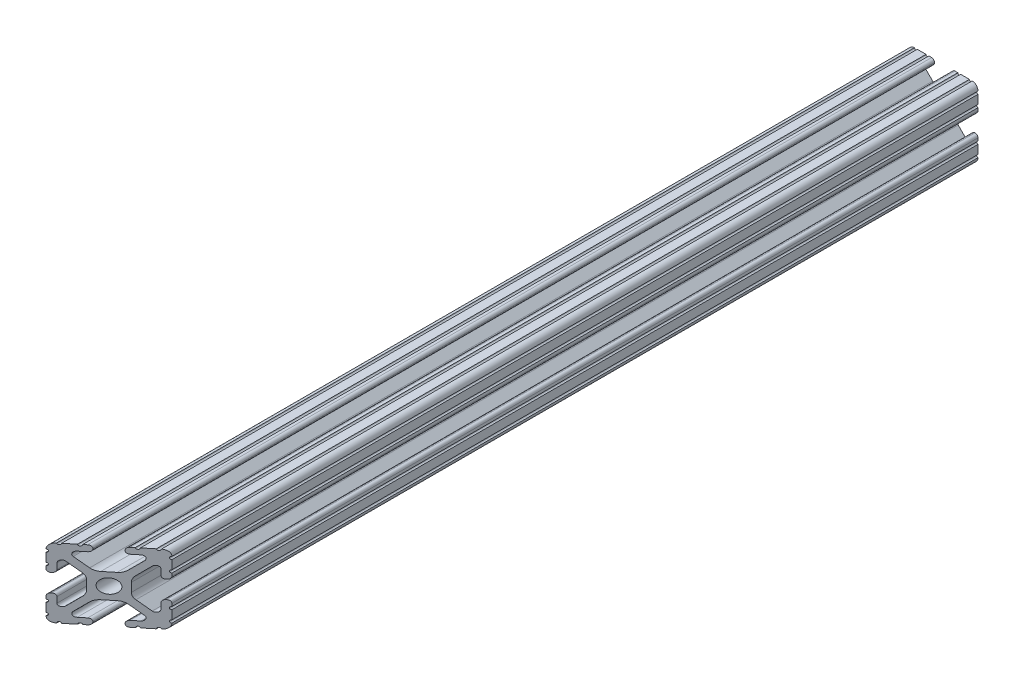
SolidWorks part; units mm, degrees
ref_plane "Front Plane" through (0, 0, 0) normal (0, 0, 1) x (1, 0, 0)
ref_plane "Top Plane" through (0, 0, 0) normal (0, 1, 0) x (1, 0, 0)
ref_plane "Right Plane" through (0, 0, 0) normal (1, 0, 0) x (0, 0, -1)
sketch "Sketch1" plane through (0, 0, 0) normal (0, 0, 1) x (1, 0, 0)
  line L88 (-7.1797, -8.6452) -> (-3.9523, -5.4237)
  line L89 (-1.7093, -4.4958) -> (1.7093, -4.4958)
  line L90 (3.9523, -5.4237) -> (7.1797, -8.6452)
  line L91 (6.4164, -10.4902) -> (4.2875, -10.4902)
  line L92 (3.2385, -11.5392) -> (3.2385, -11.651)
  line L93 (4.2875, -12.7) -> (5.3171, -12.7)
  line L94 (6.3331, -12.7) -> (9.5504, -12.7)
  line L95 (12.7, -9.5504) -> (12.7, -6.3331)
  line L96 (12.7, -5.3171) -> (12.7, -4.2875)
  line L97 (11.651, -3.2385) -> (11.5392, -3.2385)
  line L98 (10.4902, -4.2875) -> (10.4902, -6.4021)
  line L99 (8.7371, -7.1294) -> (5.441, -3.8408)
  line L100 (4.5085, -1.5932) -> (4.5085, 1.5932)
  line L101 (5.441, 3.8408) -> (8.7371, 7.1294)
  line L102 (10.4902, 6.4021) -> (10.4902, 4.2875)
  line L103 (11.5392, 3.2385) -> (11.651, 3.2385)
  line L104 (12.7, 4.2875) -> (12.7, 5.3171)
  line L105 (12.7, 6.3331) -> (12.7, 9.5504)
  line L106 (9.5504, 12.7) -> (6.3331, 12.7)
  line L107 (5.3171, 12.7) -> (4.2875, 12.7)
  line L108 (3.2385, 11.651) -> (3.2385, 11.5392)
  line L109 (4.2875, 10.4902) -> (6.4768, 10.4902)
  line L110 (7.207, 8.7244) -> (3.8983, 5.4232)
  line L111 (1.6558, 4.4958) -> (-1.6558, 4.4958)
  line L112 (-3.8983, 5.4232) -> (-7.207, 8.7244)
  line L113 (-6.4768, 10.4902) -> (-4.2875, 10.4902)
  line L114 (-3.2385, 11.5392) -> (-3.2385, 11.651)
  line L115 (-4.2875, 12.7) -> (-5.3171, 12.7)
  line L116 (-6.3331, 12.7) -> (-9.5504, 12.7)
  line L117 (-12.7, 9.5504) -> (-12.7, 6.3331)
  line L118 (-12.7, 5.3171) -> (-12.7, 4.2875)
  line L119 (-11.651, 3.2385) -> (-11.5392, 3.2385)
  line L120 (-10.4902, 4.2875) -> (-10.4902, 6.4021)
  line L121 (-8.7371, 7.1294) -> (-5.441, 3.8408)
  line L122 (-4.5085, 1.5932) -> (-4.5085, -1.5932)
  line L123 (-5.441, -3.8408) -> (-8.7371, -7.1294)
  line L124 (-10.4902, -6.4021) -> (-10.4902, -4.2875)
  line L125 (-11.5392, -3.2385) -> (-11.651, -3.2385)
  line L126 (-12.7, -4.2875) -> (-12.7, -5.3171)
  line L127 (-12.7, -6.3331) -> (-12.7, -9.5504)
  line L128 (-9.5504, -12.7) -> (-6.3331, -12.7)
  line L129 (-5.3171, -12.7) -> (-4.2875, -12.7)
  line L130 (-3.2385, -11.651) -> (-3.2385, -11.5392)
  line L131 (-4.2875, -10.4902) -> (-6.4164, -10.4902)
  circle A1 centre (0, 0) radius 2.6035
  arc A104 (-7.1797, -8.6452) -> (-6.4164, -10.4902) centre (-6.4164, -9.4098) ccw
  arc A105 (-1.7093, -4.4958) -> (-3.9523, -5.4237) centre (-1.7093, -7.6708) ccw
  arc A106 (3.9523, -5.4237) -> (1.7093, -4.4958) centre (1.7093, -7.6708) ccw
  arc A107 (6.4164, -10.4902) -> (7.1797, -8.6452) centre (6.4164, -9.4098) ccw
  arc A108 (4.2875, -10.4902) -> (3.2385, -11.5392) centre (4.2875, -11.5392) ccw
  arc A109 (3.2385, -11.651) -> (4.2875, -12.7) centre (4.2875, -11.651) ccw
  arc A110 (6.3331, -12.7) -> (5.3171, -12.7) centre (5.8251, -12.7) ccw
  arc A111 (10.5664, -12.6998) -> (9.5504, -12.7) centre (10.0584, -12.7) ccw
  arc A112 (10.5664, -12.6998) -> (12.6998, -10.5664) centre (10.5918, -10.5918) ccw
  arc A113 (12.7, -9.5504) -> (12.6998, -10.5664) centre (12.7, -10.0584) ccw
  arc A114 (12.7, -5.3171) -> (12.7, -6.3331) centre (12.7, -5.8251) ccw
  arc A115 (12.7, -4.2875) -> (11.651, -3.2385) centre (11.651, -4.2875) ccw
  arc A116 (11.5392, -3.2385) -> (10.4902, -4.2875) centre (11.5392, -4.2875) ccw
  arc A117 (8.7371, -7.1294) -> (10.4902, -6.4021) centre (9.4628, -6.4021) ccw
  arc A118 (4.5085, -1.5932) -> (5.441, -3.8408) centre (7.6835, -1.5932) ccw
  arc A119 (5.441, 3.8408) -> (4.5085, 1.5932) centre (7.6835, 1.5932) ccw
  arc A120 (10.4902, 6.4021) -> (8.7371, 7.1294) centre (9.4628, 6.4021) ccw
  arc A121 (10.4902, 4.2875) -> (11.5392, 3.2385) centre (11.5392, 4.2875) ccw
  arc A122 (11.651, 3.2385) -> (12.7, 4.2875) centre (11.651, 4.2875) ccw
  arc A123 (12.7, 6.3331) -> (12.7, 5.3171) centre (12.7, 5.8251) ccw
  arc A124 (12.6998, 10.5664) -> (12.7, 9.5504) centre (12.7, 10.0584) ccw
  arc A125 (12.6998, 10.5664) -> (10.5664, 12.6998) centre (10.5918, 10.5918) ccw
  arc A126 (9.5504, 12.7) -> (10.5664, 12.6998) centre (10.0584, 12.7) ccw
  arc A127 (5.3171, 12.7) -> (6.3331, 12.7) centre (5.8251, 12.7) ccw
  arc A128 (4.2875, 12.7) -> (3.2385, 11.651) centre (4.2875, 11.651) ccw
  arc A129 (3.2385, 11.5392) -> (4.2875, 10.4902) centre (4.2875, 11.5392) ccw
  arc A130 (7.207, 8.7244) -> (6.4768, 10.4902) centre (6.4768, 9.4563) ccw
  arc A131 (1.6558, 4.4958) -> (3.8983, 5.4232) centre (1.6558, 7.6708) ccw
  arc A132 (-3.8983, 5.4232) -> (-1.6558, 4.4958) centre (-1.6558, 7.6708) ccw
  arc A133 (-6.4768, 10.4902) -> (-7.207, 8.7244) centre (-6.4768, 9.4563) ccw
  arc A134 (-4.2875, 10.4902) -> (-3.2385, 11.5392) centre (-4.2875, 11.5392) ccw
  arc A135 (-3.2385, 11.651) -> (-4.2875, 12.7) centre (-4.2875, 11.651) ccw
  arc A136 (-6.3331, 12.7) -> (-5.3171, 12.7) centre (-5.8251, 12.7) ccw
  arc A137 (-10.5664, 12.6998) -> (-9.5504, 12.7) centre (-10.0584, 12.7) ccw
  arc A138 (-10.5664, 12.6998) -> (-12.6998, 10.5664) centre (-10.5918, 10.5918) ccw
  arc A139 (-12.7, 9.5504) -> (-12.6998, 10.5664) centre (-12.7, 10.0584) ccw
  arc A140 (-12.7, 5.3171) -> (-12.7, 6.3331) centre (-12.7, 5.8251) ccw
  arc A141 (-12.7, 4.2875) -> (-11.651, 3.2385) centre (-11.651, 4.2875) ccw
  arc A142 (-11.5392, 3.2385) -> (-10.4902, 4.2875) centre (-11.5392, 4.2875) ccw
  arc A143 (-8.7371, 7.1294) -> (-10.4902, 6.4021) centre (-9.4628, 6.4021) ccw
  arc A144 (-4.5085, 1.5932) -> (-5.441, 3.8408) centre (-7.6835, 1.5932) ccw
  arc A145 (-5.441, -3.8408) -> (-4.5085, -1.5932) centre (-7.6835, -1.5932) ccw
  arc A146 (-10.4902, -6.4021) -> (-8.7371, -7.1294) centre (-9.4628, -6.4021) ccw
  arc A147 (-10.4902, -4.2875) -> (-11.5392, -3.2385) centre (-11.5392, -4.2875) ccw
  arc A148 (-11.651, -3.2385) -> (-12.7, -4.2875) centre (-11.651, -4.2875) ccw
  arc A149 (-12.7, -6.3331) -> (-12.7, -5.3171) centre (-12.7, -5.8251) ccw
  arc A150 (-12.6998, -10.5664) -> (-12.7, -9.5504) centre (-12.7, -10.0584) ccw
  arc A151 (-12.6998, -10.5664) -> (-10.5664, -12.6998) centre (-10.5918, -10.5918) ccw
  arc A152 (-9.5504, -12.7) -> (-10.5664, -12.6998) centre (-10.0584, -12.7) ccw
  arc A153 (-5.3171, -12.7) -> (-6.3331, -12.7) centre (-5.8251, -12.7) ccw
  arc A154 (-4.2875, -12.7) -> (-3.2385, -11.651) centre (-4.2875, -11.651) ccw
  arc A155 (-3.2385, -11.5392) -> (-4.2875, -10.4902) centre (-4.2875, -11.5392) ccw
extrude "Boss-Extrude1" add sketch "Sketch1" along normal mid plane 381
sketch "Sketch2" plane through (0, 12.7, 0) normal (0, 1, 0) x (1, 0, 0)
  line L0 (-12.7, -190.5) -> (-12.7, 190.5) construction
  line L1 (-6.3331, -190.5) -> (-9.5504, -190.5) construction
  line L2 (9.5504, -190.5) -> (6.3331, -190.5) construction
  line L3 (12.7, -190.5) -> (12.7, 190.5) construction
  line L4 (-12.7, -190.5) -> (-12.7, 190.5) construction
  line L5 (-6.3331, -190.5) -> (-9.5504, -190.5) construction
  line L6 (9.5504, -190.5) -> (6.3331, -190.5) construction
  line L7 (12.7, -190.5) -> (12.7, 190.5) construction
  line L8 (12.7, -190.5) -> (-12.7, -190.5)
  line L9 (-12.7, -190.5) -> (-12.7, -125.5716)
  line L10 (-12.7, -125.5716) -> (12.7, -104.8312)
  line L11 (12.7, -104.8312) -> (12.7, -190.5)
extrude "Cut-Extrude1" cut sketch "Sketch2" against normal through all
